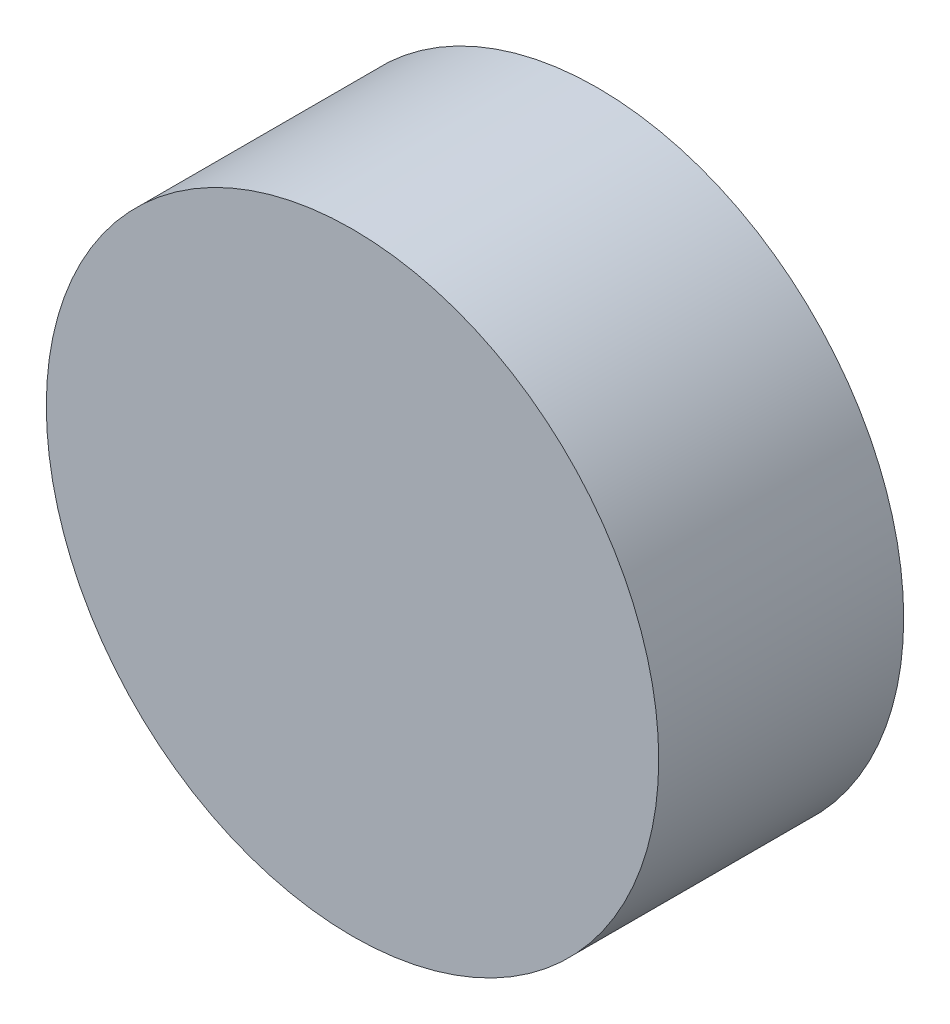
SolidWorks part; units mm, degrees
ref_plane "前视基准面" through (0, 0, 0) normal (0, 0, 1) x (1, 0, 0)
ref_plane "上视基准面" through (0, 0, 0) normal (0, 1, 0) x (1, 0, 0)
ref_plane "右视基准面" through (0, 0, 0) normal (1, 0, 0) x (0, 0, -1)
sketch "草图1" plane through (0, 0, 0) normal (0, 0, 1) x (1, 0, 0)
  circle A0 centre (0, 0) radius 5
extrude "凸台-拉伸1" add sketch "草图1" along normal blind 4
